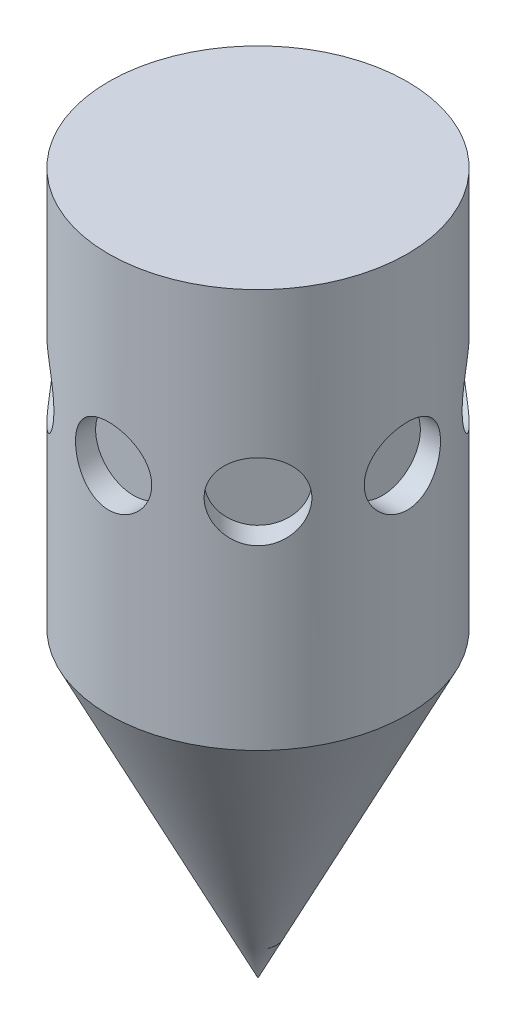
SolidWorks part; units mm, degrees
ref_plane "Front Plane" through (0, 0, 0) normal (0, 0, 1) x (1, 0, 0)
ref_plane "Top Plane" through (0, 0, 0) normal (0, 1, 0) x (1, 0, 0)
ref_plane "Right Plane" through (0, 0, 0) normal (1, 0, 0) x (0, 0, -1)
other "Configuration Table"
sketch "Sketch1" plane through (0, 0, 0) normal (0, 0, 1) x (1, 0, 0)
  line L0 (-29.8366, 70.1062) -> (0, 70.1062)
  line L1 (0, 70.1062) -> (0, -39.6846)
  line L2 (0, -32.8202) -> (0, 32.8202) construction
  line L3 (-15.0158, -39.6846) -> (0, -70.1113)
  line L4 (-15.0158, -39.6846) -> (-29.8366, -9.653)
  line L5 (-29.8366, -9.653) -> (-29.8366, 70.1062)
  line L6 (0, -39.6846) -> (0, -70.1113)
revolve "Revolve1" add sketch "Sketch1" angle 360 about L1
ref_plane "Plane1" through (0, 0, 29.8366) normal (0, 0, 1) x (1, 0, 0)
sketch "Sketch2" plane through (0, 0, 29.8366) normal (0, 0, 1) x (1, 0, 0)
  line L0 (0, -32.8202) -> (0, 32.8202) construction
  circle A0 centre (0, 33.4066) radius 7.6154
extrude "Cut-Extrude1" cut sketch "Sketch2" against normal blind 5
pattern_circular "CirPattern1" count 8 every 45 about axis through (0, 0, 0) along (0, 1, 0) of "Cut-Extrude1"
